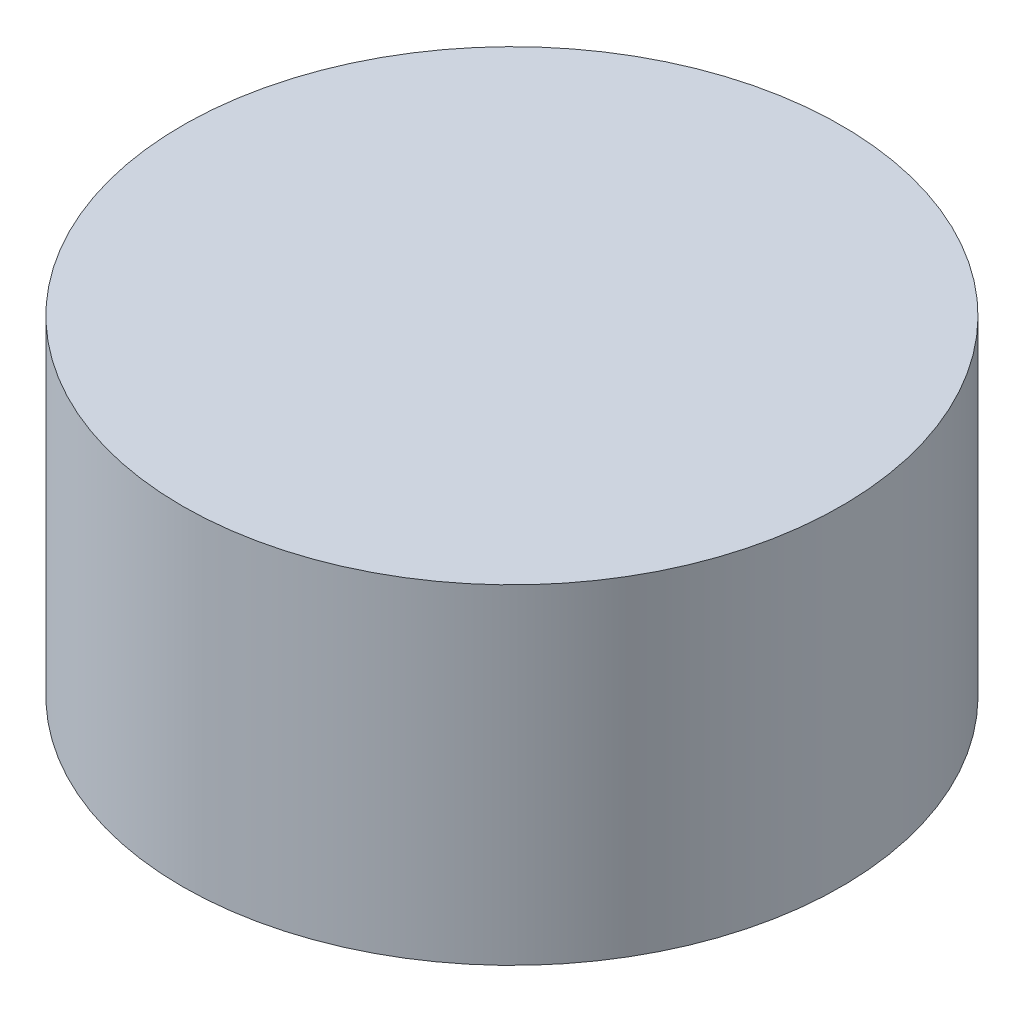
SolidWorks part; units mm, degrees
ref_plane "Front Plane" through (0, 0, 0) normal (0, 0, 1) x (1, 0, 0)
ref_plane "Top Plane" through (0, 0, 0) normal (0, 1, 0) x (1, 0, 0)
ref_plane "Right Plane" through (0, 0, 0) normal (1, 0, 0) x (0, 0, -1)
other "Configuration Table"
sketch "Sketch1" plane through (0, 0, 0) normal (0, 1, 0) x (1, 0, 0)
  circle A0 centre (0, 0) radius 35
extrude "KOLA1L_omuz_D70" add sketch "Sketch1" along normal blind 35 from offset 190 separate body
